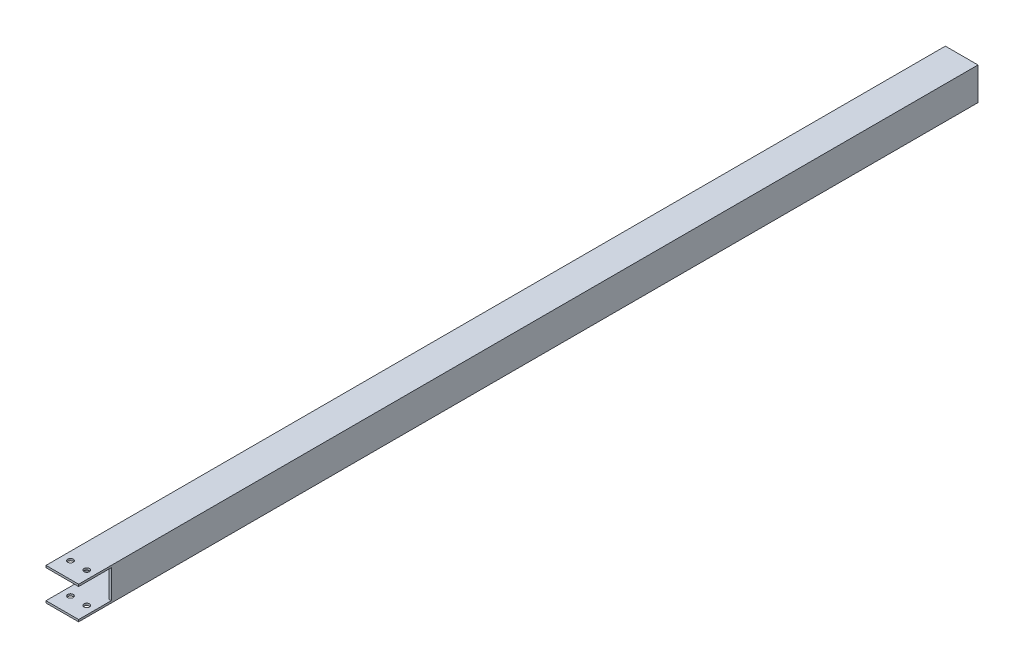
SolidWorks part; units mm, degrees
ref_plane "Plan de face" through (0, 0, 0) normal (0, 0, 1) x (1, 0, 0)
ref_plane "Plan de dessus" through (0, 0, 0) normal (0, 1, 0) x (1, 0, 0)
ref_plane "Plan de droite" through (0, 0, 0) normal (1, 0, 0) x (0, 0, -1)
sketch "Esquisse1" plane through (0, 0, 0) normal (0, 0, 1) x (1, 0, 0)
  line L1 (-12.7, 12.7) -> (12.7, 12.7)
  line L2 (-12.7, 12.7) -> (-12.7, -12.7)
  line L3 (-12.7, -12.7) -> (12.7, -12.7)
  line L4 (12.7, 12.7) -> (12.7, -12.7)
  line L5 (-12.7, 12.7) -> (12.7, -12.7) construction
  line L6 (-12.7, -12.7) -> (12.7, 12.7) construction
  line L7 (-11.1125, 11.1125) -> (11.1125, 11.1125)
  line L8 (-11.1125, 11.1125) -> (-11.1125, -11.1125)
  line L9 (-11.1125, -11.1125) -> (11.1125, -11.1125)
  line L10 (11.1125, 11.1125) -> (11.1125, -11.1125)
  line L11 (-11.1125, 11.1125) -> (11.1125, -11.1125) construction
  line L12 (-11.1125, -11.1125) -> (11.1125, 11.1125) construction
  point P0 (0, 0)
  point P6 (0, 0)
  dimension "D1" = 25.4
  dimension "D2" = 25.4
  dimension "D3" = 1.5875
extrude "Boss.-Extru.1" add sketch "Esquisse1" along normal mid plane 700
sketch "Esquisse2" plane through (0, -12.7, 0) normal (0, -1, 0) x (1, 0, 0)
  line L0 (12.7, 350) -> (12.7, -350) construction
  line L1 (-12.7, 350) -> (12.7, 350) construction
  circle A0 centre (6.35, 337.3) radius 2.159
  dimension "D1" = 4.318
  dimension "D2" = 6.35
  dimension "D3" = 12.7
extrude "Enlèv. mat.-Extru.1" cut sketch "Esquisse2" against normal through all
mirror "Symétrie1" about plane through (0, 0, 0) normal (1, 0, 0) of "Enlèv. mat.-Extru.1"
sketch "Esquisse3" plane through (12.7, 0, 0) normal (1, 0, 0) x (0, 0, -1)
  line L0 (-350, -12.7) -> (-350, 12.7) construction
  line L1 (-350, 11.1125) -> (-324.6, 11.1125)
  line L2 (-350, 11.1125) -> (-350, -11.1125)
  line L3 (-350, -11.1125) -> (-324.6, -11.1125)
  line L4 (-324.6, 11.1125) -> (-324.6, -11.1125)
  line L5 (-350, -12.7) -> (350, -12.7) construction
  dimension "D1" = 22.225
  dimension "D2" = 1.5875
  dimension "D3" = 25.4
extrude "Enlèv. mat.-Extru.3" cut sketch "Esquisse3" against normal through all
